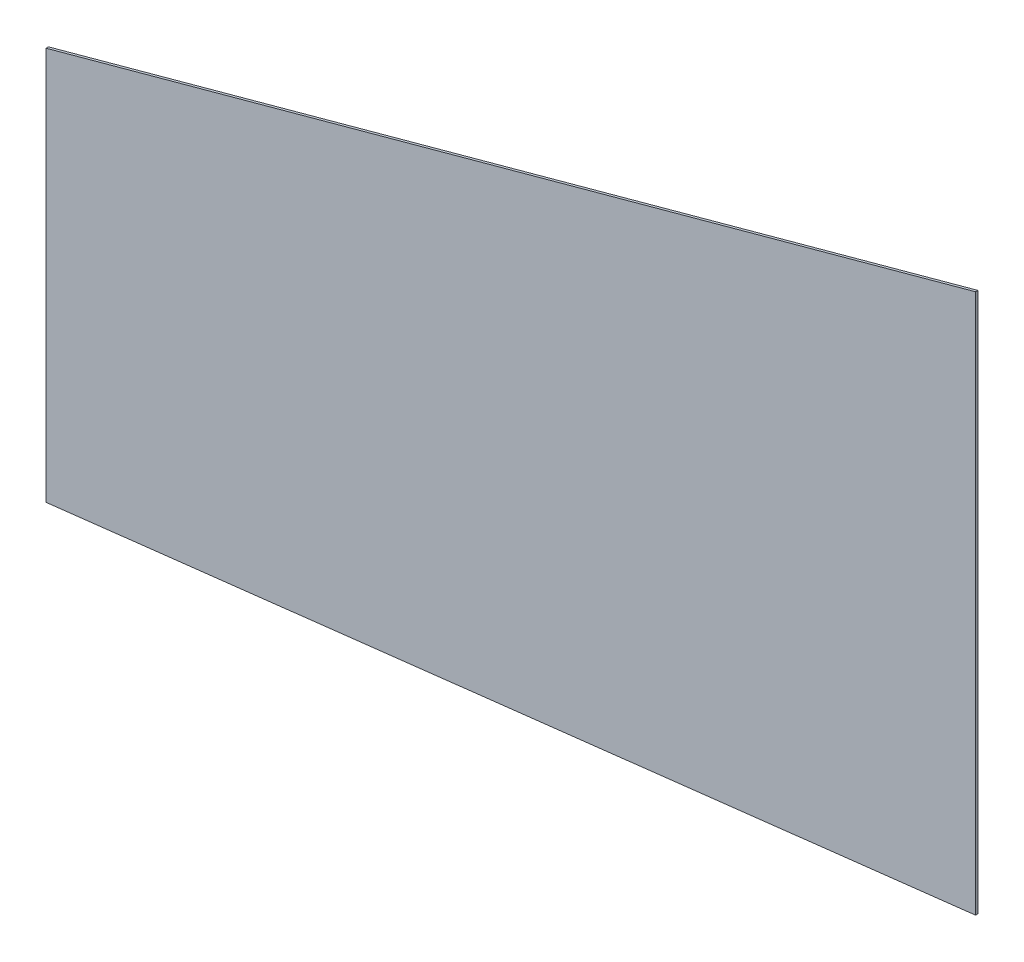
SolidWorks part; units mm, degrees
ref_plane "正面" through (0, 0, 0) normal (0, 0, 1) x (1, 0, 0)
ref_plane "平面" through (0, 0, 0) normal (0, 1, 0) x (1, 0, 0)
ref_plane "右側面" through (0, 0, 0) normal (1, 0, 0) x (0, 0, -1)
sketch "ｽｹｯﾁ1" plane through (0, 0, 0) normal (0, 0, 1) x (1, 0, 0)
  line L0 (0, 330) -> (0, 0)
  line L1 (0, 0) -> (1012.0775, 0) construction
  line L2 (0, 0) -> (780, 90)
  line L3 (780, 90) -> (780, 543)
  line L4 (780, 543) -> (0, 330)
  dimension "D1" = 330
  dimension "D2" = 780
  dimension "D3" = 90
  dimension "D4" = 453
extrude "ﾎﾞｽ - 押し出し1" add sketch "ｽｹｯﾁ1" along normal blind 2
